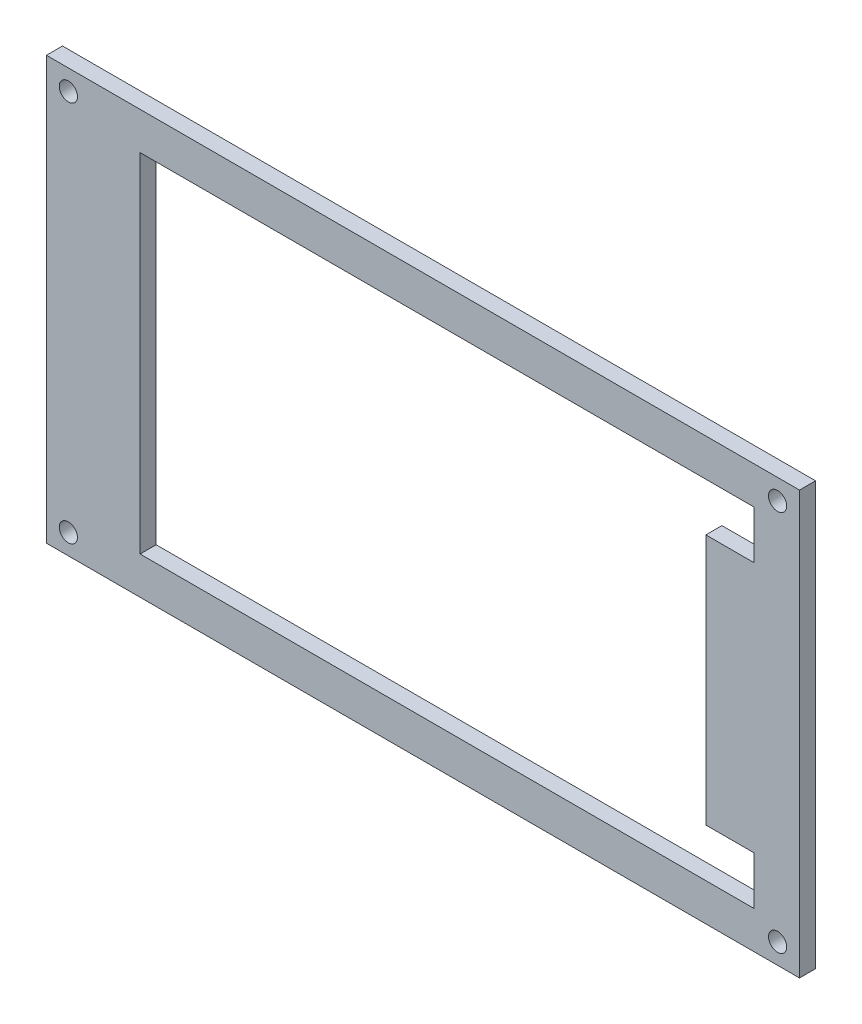
SolidWorks part; units mm, degrees
ref_plane "前视基准面" through (0, 0, 0) normal (0, 0, 1) x (1, 0, 0)
ref_plane "上视基准面" through (0, 0, 0) normal (0, 1, 0) x (1, 0, 0)
ref_plane "右视基准面" through (0, 0, 0) normal (1, 0, 0) x (0, 0, -1)
other "Configuration Table"
sketch "草图1" plane through (0, 0, 0) normal (0, 0, 1) x (1, 0, 0)
  line L0 (-70.35, 0) -> (70.35, 0) construction
  line L1 (-70.35, 39.475) -> (70.35, 39.475)
  line L2 (-70.35, 39.475) -> (-70.35, -39.475)
  line L3 (-70.35, -39.475) -> (70.35, -39.475)
  line L4 (70.35, 39.475) -> (70.35, -39.475)
  line L5 (-70.35, 39.475) -> (70.35, -39.475) construction
  line L6 (-70.35, -39.475) -> (70.35, 39.475) construction
  line L7 (0, -39.475) -> (0, 39.475) construction
  circle A0 centre (-66.2527, 35.6683) radius 1.7
  circle A1 centre (66.2527, 35.6683) radius 1.7
  circle A2 centre (66.2527, -35.6683) radius 1.7
  circle A3 centre (-66.2527, -35.6683) radius 1.7
  point P0 (0, 0)
  dimension "D1" = 78.95
  dimension "D2" = 140.7
extrude "凸台-拉伸1" add sketch "草图1" along normal blind 3
sketch "草图2" plane through (0, 0, 3) normal (0, 0, 1) x (1, 0, 0)
  line L0 (70.35, 39.475) -> (-70.35, 39.475) construction
  line L1 (-52.85, 32.475) -> (52.85, 32.475)
  line L2 (-52.85, 32.475) -> (-52.85, -32.475)
  line L3 (-52.85, -32.475) -> (52.85, -32.475)
  line L4 (52.85, 32.475) -> (52.85, -32.475)
  line L5 (-70.35, -39.475) -> (70.35, -39.475) construction
  line L6 (-70.35, 39.475) -> (-70.35, -39.475) construction
  line L7 (70.35, -39.475) -> (70.35, 39.475) construction
  dimension "D1" = 7
  dimension "D2" = 7
  dimension "D3" = 17.5
  dimension "D4" = 17.5
extrude "切除-拉伸1" cut sketch "草图2" against normal through all
sketch "草图3" plane through (0, 0, 3) normal (0, 0, 1) x (1, 0, 0)
  line L0 (0, 0) -> (70.35, 0) construction
  line L1 (52.85, 32.475) -> (61.85, 32.475)
  line L2 (52.85, 32.475) -> (52.85, 23.475)
  line L3 (52.85, 23.475) -> (61.85, 23.475)
  line L4 (61.85, 32.475) -> (61.85, 23.475)
  line L5 (70.35, -39.475) -> (70.35, 39.475) construction
  line L6 (52.85, -23.475) -> (61.85, -23.475)
  line L7 (61.85, -32.475) -> (61.85, -23.475)
  line L8 (52.85, -32.475) -> (61.85, -32.475)
  line L9 (52.85, -32.475) -> (52.85, -23.475)
  dimension "D1" = 9
  dimension "D2" = 9
extrude "切除-拉伸2" cut sketch "草图3" against normal through all
